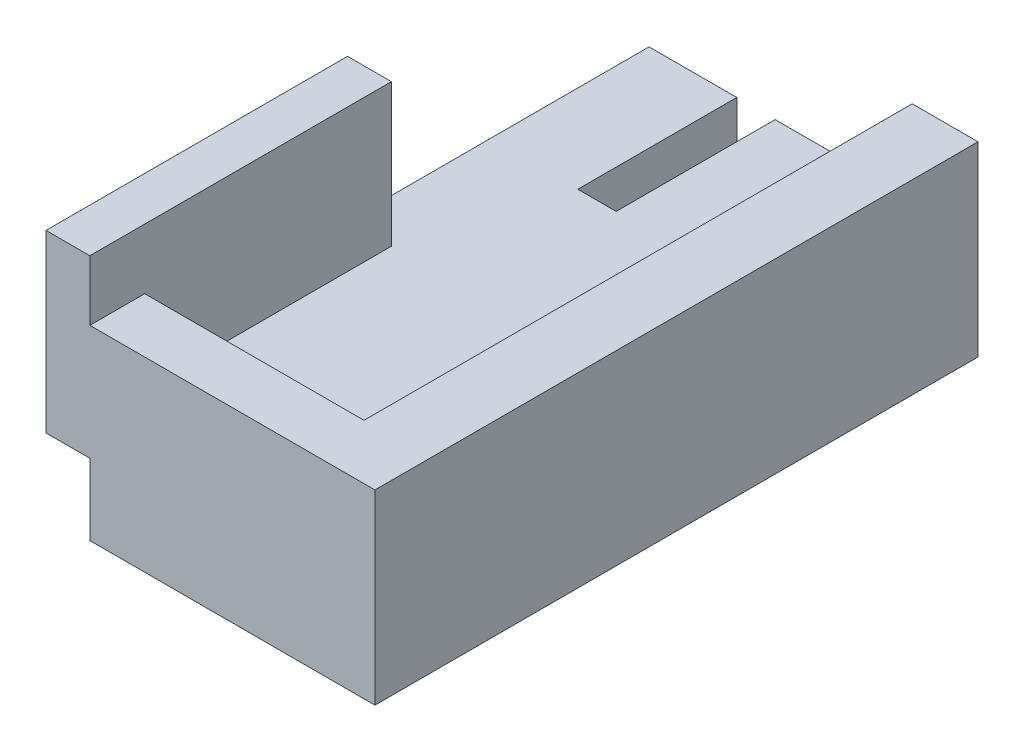
SolidWorks part; units mm, degrees
ref_plane "Спереди" through (0, 0, 0) normal (0, 0, 1) x (1, 0, 0)
ref_plane "Сверху" through (0, 0, 0) normal (0, 1, 0) x (1, 0, 0)
ref_plane "Справа" through (0, 0, 0) normal (1, 0, 0) x (0, 0, -1)
sketch "Эскиз1" plane through (0, 0, 0) normal (0, 0, 1) x (1, 0, 0)
  line L1 (-32.5, -22.5) -> (32.5, -22.5)
  line L2 (-32.5, -22.5) -> (-32.5, 22.5)
  line L3 (-32.5, 22.5) -> (32.5, 22.5)
  line L4 (32.5, -22.5) -> (32.5, 22.5)
  line L5 (-32.5, -22.5) -> (32.5, 22.5) construction
  line L6 (-32.5, 22.5) -> (32.5, -22.5) construction
  line L7 (32.5, 22.5) -> (27.5, 22.5)
  line L8 (32.5, 22.5) -> (32.5, -6.5)
  line L9 (32.5, -6.5) -> (27.5, -6.5)
  line L10 (27.5, 22.5) -> (27.5, -6.5)
  line L11 (-24.5, 22.5) -> (27.5, 22.5)
  line L12 (-24.5, 22.5) -> (-24.5, 11.5)
  line L13 (-24.5, 11.5) -> (27.5, 11.5)
  line L14 (27.5, 22.5) -> (27.5, 11.5)
  point P0 (0, 0)
  dimension "D1" = 65
  dimension "D2" = 45
  dimension "D3" = 5
  dimension "D4" = 29
  dimension "D5" = 8
  dimension "D6" = 11
extrude "Бобышка-Вытянуть1" add sketch "Эскиз1" along normal blind 110 contours L13 L12 L3 L2 L1 L4 L9 L10
sketch "Эскиз2" plane through (0, 0, 110) normal (0, 0, 1) x (1, 0, 0)
  line L1 (-32.5, -22.5) -> (-24.5, -22.5)
  line L2 (-32.5, -22.5) -> (-32.5, -9.5)
  line L3 (-32.5, -9.5) -> (-24.5, -9.5)
  line L4 (-24.5, -22.5) -> (-24.5, -9.5)
  line L5 (-32.5, 22.5) -> (-24.5, 22.5) construction
  line L6 (-24.5, 22.5) -> (-24.5, 11.5) construction
  dimension "D1" = 13
extrude "Вырез-Вытянуть1" cut sketch "Эскиз2" against normal blind 14
sketch "Эскиз3" plane through (-32.5, 0, 0) normal (1, 0, 0) x (0, 0, -1)
  line L0 (-55, -22.5) -> (-55, 22.5) construction
  line L1 (-110, -22.5) -> (0, -22.5) construction
  line L2 (-110, 22.5) -> (0, 22.5) construction
  line L4 (-67.5, -22.5) -> (-42.5, -22.5)
  line L5 (-67.5, -22.5) -> (-67.5, -16.5)
  line L6 (-67.5, -16.5) -> (-42.5, -16.5)
  line L7 (-42.5, -22.5) -> (-42.5, -16.5)
  line L8 (-67.5, -22.5) -> (-42.5, -16.5) construction
  line L9 (-67.5, -16.5) -> (-42.5, -22.5) construction
  point P6 (-55, -19.5)
  dimension "D1" = 6
  dimension "D2" = 25
sketch "Эскиз4" plane through (0, 11.5, 0) normal (0, 1, 0) x (1, 0, 0)
  line L0 (-24.5, -110) -> (-24.5, 0) construction
  line L1 (-24.5, -100) -> (15.5, -100)
  line L2 (-24.5, -100) -> (-24.5, 0)
  line L3 (-24.5, 0) -> (15.5, 0)
  line L4 (15.5, -100) -> (15.5, 0)
  line L5 (-24.5, 0) -> (27.5, 0) construction
  line L6 (-32.5, -110) -> (-32.5, 0) construction
  line L7 (-24.5, 0) -> (-32.5, 0)
  line L8 (-24.5, 0) -> (-24.5, -55)
  line L9 (-24.5, -55) -> (-32.5, -55)
  line L10 (-32.5, 0) -> (-32.5, -55)
  line M1 (27.5, 0) -> (-24.5, 0)
  line M2 (-24.5, 0) -> (-24.5, -110)
  dimension "D1" = 40
  dimension "D2" = 100
extrude "Вырез-Вытянуть4" cut sketch "Эскиз4" against normal blind 15 and the other way through all contours L1 L4 L2 M1 M2 | L7 L10 L9 M2
sketch "Эскиз5" plane through (0, 0, 0) normal (0, 0, -1) x (-1, 0, 0)
  line L0 (32.5, -22.5) -> (32.5, -3.5) construction
  line L1 (16.5, -3.5) -> (9.5, -3.5)
  line L2 (16.5, -3.5) -> (16.5, -10.5)
  line L3 (16.5, -10.5) -> (9.5, -10.5)
  line L4 (9.5, -3.5) -> (9.5, -10.5)
  line L5 (24.5, -3.5) -> (-15.5, -3.5) construction
  dimension "D1" = 7
  dimension "D2" = 16
extrude "Вырез-Вытянуть5" cut sketch "Эскиз5" against normal blind 29
extrude "Вырез-Вытянуть6" cut sketch "Эскиз3" along normal blind 10
sketch "Эскиз6" plane through (0, -6.5, 0) normal (0, 1, 0) x (1, 0, 0)
  line L4 (32.5, 0) -> (27.5, 0)
  line L5 (27.5, 0) -> (27.5, -110)
  line L6 (27.5, -110) -> (32.5, -110)
  line L7 (32.5, -110) -> (32.5, 0)
  line L8 (32.5, 0) -> (27.5, 0)
  line L9 (27.5, 0) -> (27.5, -110)
  line L10 (27.5, -110) -> (32.5, -110)
  line L11 (32.5, -110) -> (32.5, 0)
  dimension "D1" = 0
extrude "Вырез-Вытянуть7" cut sketch "Эскиз6" against normal through all
